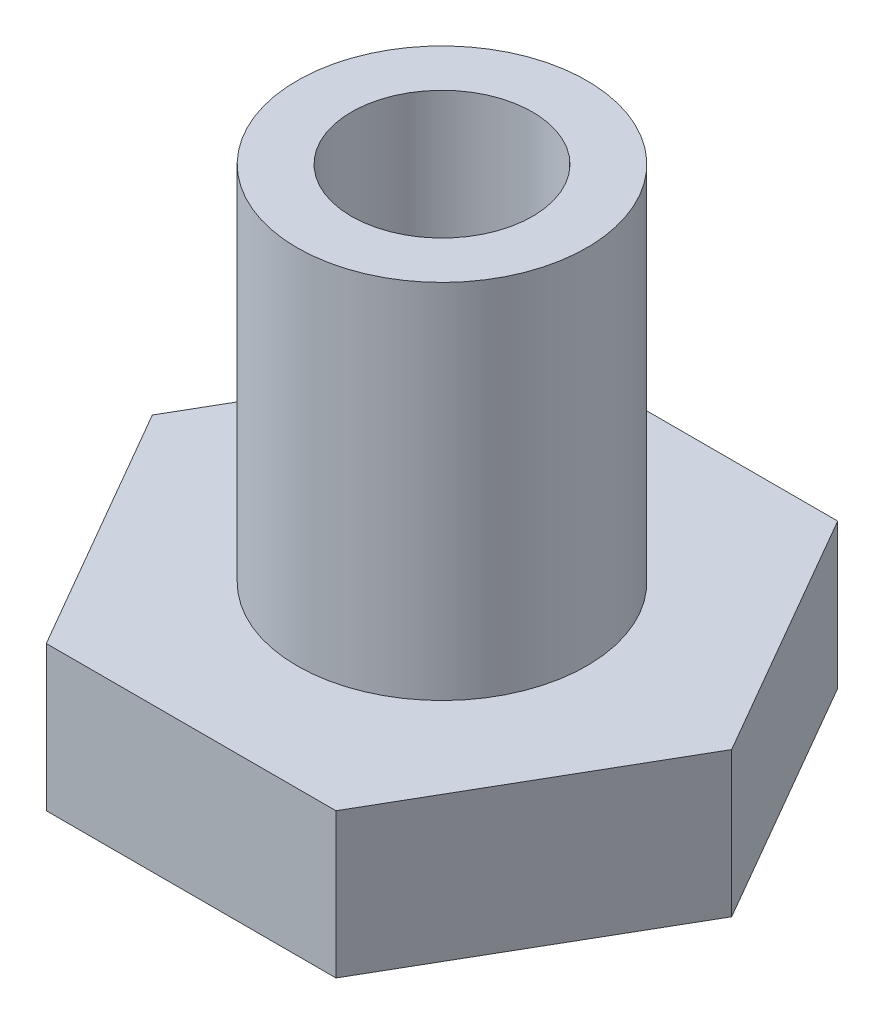
SolidWorks part; units mm, degrees
ref_plane "前视基准面" through (0, 0, 0) normal (0, 0, 1) x (1, 0, 0)
ref_plane "上视基准面" through (0, 0, 0) normal (0, 1, 0) x (1, 0, 0)
ref_plane "右视基准面" through (0, 0, 0) normal (1, 0, 0) x (0, 0, -1)
sketch "草图1" plane through (0, 0, 0) normal (0, 1, 0) x (1, 0, 0)
  line L1 (8, -13.8564) -> (16, 0)
  line L2 (16, 0) -> (8, 13.8564)
  line L3 (8, 13.8564) -> (-8, 13.8564)
  line L4 (-8, 13.8564) -> (-16, 0)
  line L5 (-16, 0) -> (-8, -13.8564)
  line L6 (-8, -13.8564) -> (8, -13.8564)
  circle A0 centre (0, 0) radius 13.8564 construction
  dimension "D1" = 16
  dimension "D2" = 32
extrude "凸台-拉伸2" add sketch "草图1" along normal blind 8
sketch "草图3" plane through (0, 8, 0) normal (0, 1, 0) x (1, 0, 0)
  circle A0 centre (0, 0) radius 8
  dimension "D1" = 16
extrude "凸台-拉伸3" add sketch "草图3" along normal blind 20 contours A0
sketch "草图4" plane through (0, 28, 0) normal (0, 1, 0) x (1, 0, 0)
  circle A0 centre (0, 0) radius 5
  dimension "D1" = 10
extrude "切除-拉伸1" cut sketch "草图4" against normal blind 20
